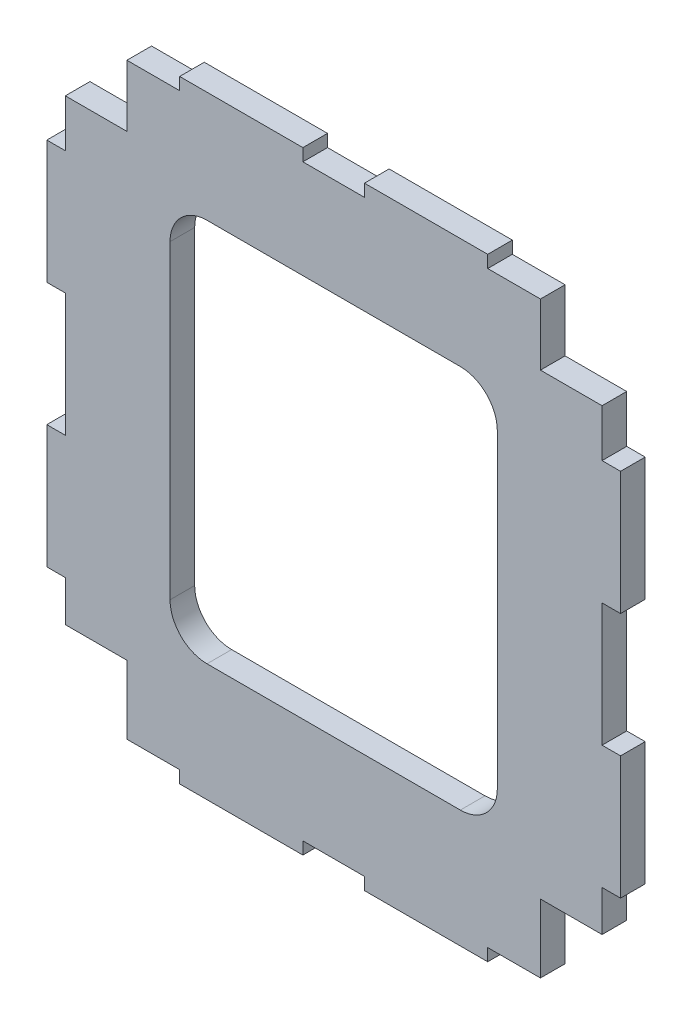
SolidWorks part; units mm, degrees
ref_plane "前视基准面" through (0, 0, 0) normal (0, 0, 1) x (1, 0, 0)
ref_plane "上视基准面" through (0, 0, 0) normal (0, 1, 0) x (1, 0, 0)
ref_plane "右视基准面" through (0, 0, 0) normal (1, 0, 0) x (0, 0, -1)
sketch "Model" plane through (0, 0, 0) normal (0, 0, 1) x (1, 0, 0)
  line L0 (48.679, 46.6105) -> (28.119, 46.6105)
  line L1 (51.679, 43.6105) -> (51.679, 18.4405)
  line L2 (28.119, 15.4405) -> (48.679, 15.4405)
  line L3 (25.119, 43.6105) -> (25.119, 18.4405)
  line L4 (21.619, 54.6105) -> (25.899, 54.6105)
  line L5 (25.899, 54.6105) -> (25.899, 55.6109)
  line L6 (25.899, 55.6109) -> (35.899, 55.6109)
  line L7 (35.899, 55.6109) -> (35.899, 54.6105)
  line L8 (35.899, 54.6105) -> (40.899, 54.6105)
  line L9 (40.899, 54.6105) -> (40.899, 55.6109)
  line L10 (40.899, 55.6109) -> (50.899, 55.6109)
  line L11 (50.899, 55.6109) -> (50.899, 54.6105)
  line L12 (50.899, 54.6105) -> (55.179, 54.6105)
  line L13 (15.119, 15.7505) -> (15.119, 25.7505)
  line L14 (15.119, 35.7505) -> (15.119, 45.7505)
  line L15 (16.619, 49.6105) -> (21.619, 49.6105)
  line L16 (21.619, 49.6105) -> (21.619, 54.6105)
  line L17 (16.619, 12.4405) -> (21.619, 12.4405)
  line L18 (21.619, 12.4405) -> (21.619, 6.8876)
  line L19 (16.619, 49.6105) -> (16.619, 45.7505)
  line L20 (16.619, 45.7505) -> (15.119, 45.7505)
  line L21 (15.119, 35.7505) -> (16.619, 35.7505)
  line L22 (16.619, 35.7505) -> (16.619, 25.7505)
  line L23 (16.619, 25.7505) -> (15.119, 25.7505)
  line L24 (15.119, 15.7505) -> (16.619, 15.7505)
  line L25 (16.619, 15.7505) -> (16.619, 12.4405)
  line L26 (21.619, 6.8876) -> (25.899, 6.8876)
  line L27 (25.899, 6.8876) -> (25.899, 5.8873)
  line L28 (25.899, 5.8873) -> (35.899, 5.8873)
  line L29 (35.899, 5.8873) -> (35.899, 6.8876)
  line L30 (35.899, 6.8876) -> (40.899, 6.8876)
  line L31 (40.899, 6.8876) -> (40.899, 5.8873)
  line L32 (40.899, 5.8873) -> (50.899, 5.8873)
  line L33 (50.899, 5.8873) -> (50.899, 6.8876)
  line L34 (50.899, 6.8876) -> (55.179, 6.8876)
  line L35 (61.679, 15.7505) -> (61.679, 25.7505)
  line L36 (61.679, 35.7505) -> (61.679, 45.7505)
  line L37 (60.179, 49.6105) -> (55.179, 49.6105)
  line L38 (55.179, 49.6105) -> (55.179, 54.6105)
  line L39 (60.179, 12.4405) -> (55.179, 12.4405)
  line L40 (55.179, 12.4405) -> (55.179, 6.8876)
  line L41 (60.179, 49.6105) -> (60.179, 45.7505)
  line L42 (60.179, 45.7505) -> (61.679, 45.7505)
  line L43 (61.679, 35.7505) -> (60.179, 35.7505)
  line L44 (60.179, 35.7505) -> (60.179, 25.7505)
  line L45 (60.179, 25.7505) -> (61.679, 25.7505)
  line L46 (61.679, 15.7505) -> (60.179, 15.7505)
  line L47 (60.179, 15.7505) -> (60.179, 12.4405)
  arc A0 (28.119, 46.6105) -> (25.119, 43.6105) centre (28.119, 43.6105) ccw
  arc A1 (51.679, 43.6105) -> (48.679, 46.6105) centre (48.679, 43.6105) ccw
  arc A2 (25.119, 18.4405) -> (28.119, 15.4405) centre (28.119, 18.4405) ccw
  arc A3 (48.679, 15.4405) -> (51.679, 18.4405) centre (48.679, 18.4405) ccw
extrude "凸台-拉伸1" add sketch "Model" along normal blind 2
